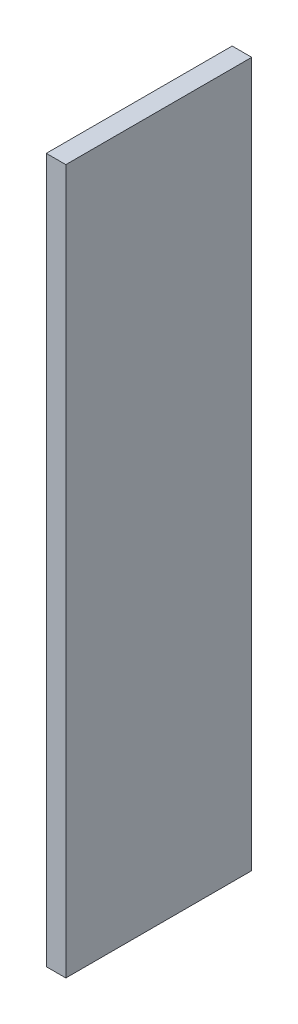
SolidWorks part; units mm, degrees
ref_plane "Front Plane" through (0, 0, 0) normal (0, 0, 1) x (1, 0, 0)
ref_plane "Top Plane" through (0, 0, 0) normal (0, 1, 0) x (1, 0, 0)
ref_plane "Right Plane" through (0, 0, 0) normal (1, 0, 0) x (0, 0, -1)
sketch "Sketch1" plane through (0, 25.4, 0) normal (0, 1, 0) x (1, 0, 0)
  line L0 (304.8, 69.85) -> (-304.8, 69.85) construction
  line L1 (-304.8, -50.8) -> (-292.1, -50.8)
  line L2 (-304.8, -50.8) -> (-304.8, 69.85)
  line L3 (-304.8, 69.85) -> (-292.1, 69.85)
  line L4 (-292.1, -50.8) -> (-292.1, 69.85)
  dimension "D1" = 12.7
extrude "Boss-Extrude1" add sketch "Sketch1" along normal blind 457.2
